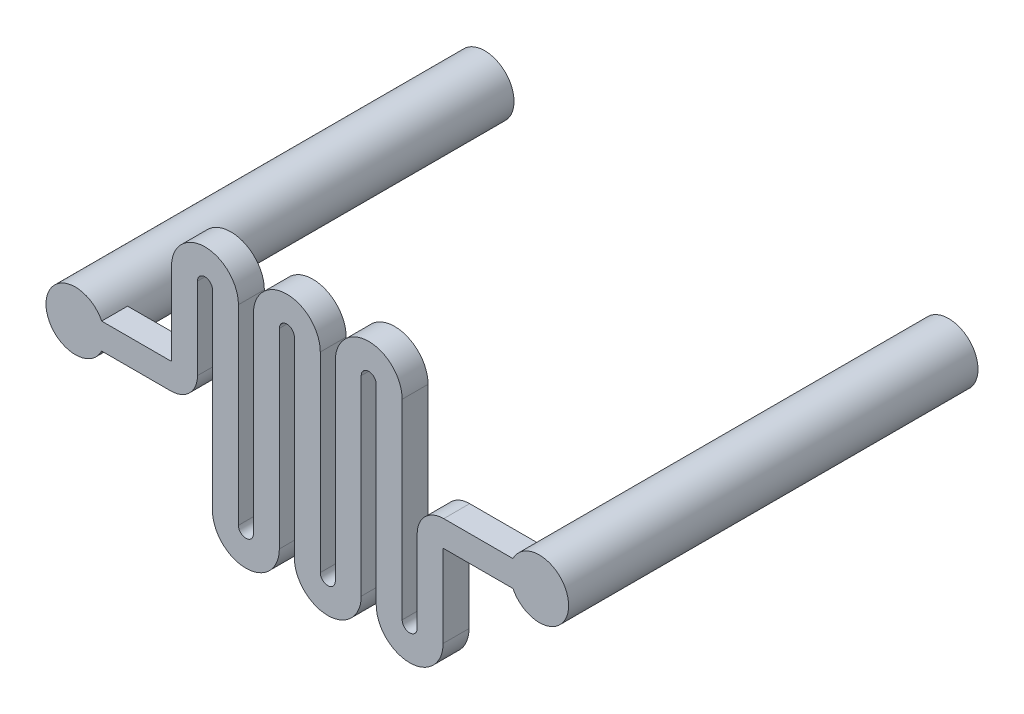
SolidWorks part; units mm, degrees
ref_plane "Front Plane" through (0, 0, 0) normal (0, 0, 1) x (1, 0, 0)
ref_plane "Top Plane" through (0, 0, 0) normal (0, 1, 0) x (1, 0, 0)
ref_plane "Right Plane" through (0, 0, 0) normal (1, 0, 0) x (0, 0, -1)
sketch "Sketch2" plane through (0, 0, 0) normal (0, 0, 1) x (1, 0, 0)
  line L3 (-20.5, -0.95) -> (-13.5, -0.95)
  line L6 (-11.55, 1) -> (-11.55, 7)
  line L9 (-10.45, 7) -> (-10.45, 0)
  line L12 (-10.45, 0) -> (-10.45, -7)
  line L15 (-5.55, -7) -> (-5.55, 0)
  line L18 (-5.55, 0) -> (-5.55, 7)
  line L21 (-4.45, 7) -> (-4.45, 0)
  line L22 (-4.45, 0) -> (-4.45, -7)
  line L23 (0.45, -7) -> (0.45, 0)
  line L24 (0.45, 0) -> (0.45, 7)
  line L25 (1.55, 7) -> (1.55, 0)
  line L26 (1.55, 0) -> (1.55, -7)
  line L27 (6.45, -7) -> (6.45, -1)
  line L28 (6.5, -0.95) -> (13.5, -0.95)
  line L29 (-20.5, 0.95) -> (-13.5, 0.95)
  line L30 (-13.45, 1) -> (-13.45, 7)
  line L31 (-8.55, 7) -> (-8.55, 0)
  line L32 (-8.55, 0) -> (-8.55, -7)
  line L33 (-7.45, -7) -> (-7.45, 0)
  line L34 (-7.45, 0) -> (-7.45, 7)
  line L35 (-2.55, 7) -> (-2.55, 0)
  line L36 (-2.55, 0) -> (-2.55, -7)
  line L37 (-1.45, -7) -> (-1.45, 0)
  line L38 (-1.45, 0) -> (-1.45, 7)
  line L39 (3.45, 7) -> (3.45, 0)
  line L40 (3.45, 0) -> (3.45, -7)
  line L41 (4.55, -7) -> (4.55, -1)
  line L42 (6.5, 0.95) -> (13.5, 0.95)
  arc A0 (13.5, -0.95) -> (13.5, 0.95) centre (13.5, 0) ccw
  arc A8 (-11.55, 1) -> (-13.5, -0.95) centre (-13.5, 1) cw
  arc A9 (-11.55, 7) -> (-10.45, 7) centre (-11, 7) cw
  arc A10 (-10.45, -7) -> (-5.55, -7) centre (-8, -7) ccw
  arc A11 (-5.55, 7) -> (-4.45, 7) centre (-5, 7) cw
  arc A12 (-4.45, -7) -> (0.45, -7) centre (-2, -7) ccw
  arc A13 (0.45, 7) -> (1.55, 7) centre (1, 7) cw
  arc A14 (1.55, -7) -> (6.45, -7) centre (4, -7) ccw
  arc A15 (6.45, -1) -> (6.5, -0.95) centre (6.5, -1) cw
  arc A16 (-13.45, 1) -> (-13.5, 0.95) centre (-13.5, 1) cw
  arc A17 (-13.45, 7) -> (-8.55, 7) centre (-11, 7) cw
  arc A18 (-8.55, -7) -> (-7.45, -7) centre (-8, -7) ccw
  arc A19 (-7.45, 7) -> (-2.55, 7) centre (-5, 7) cw
  arc A20 (-2.55, -7) -> (-1.45, -7) centre (-2, -7) ccw
  arc A21 (-1.45, 7) -> (3.45, 7) centre (1, 7) cw
  arc A22 (3.45, -7) -> (4.55, -7) centre (4, -7) ccw
  arc A23 (4.55, -1) -> (6.5, 0.95) centre (6.5, -1) cw
  arc A24 (-20.5, 0.95) -> (-20.5, -0.95) centre (-20.5, 0) ccw
  point P4 (0, 0)
  point P32 (5.5, 0)
  point P35 (-12.5, 0)
extrude "Boss-Extrude1" add sketch "Sketch2" along normal blind 1.9
ref_plane "Plane1" through (0, 0, 0) normal (0, 1, 0) x (1, 0, 0)
ref_plane "Plane2" through (0, 0, 0) normal (0, 1, 0) x (1, 0, 0)
sketch "Sketch4" plane through (0, 0, 0) normal (0, 1, 0) x (1, 0, 0)
  line L1 (13.5, 28.1) -> (15.65, 28.1)
  line L2 (13.5, -1.9) -> (13.5, 28.1)
  line L3 (15.65, 28.1) -> (15.65, -1.9)
  line L7 (15.65, -1.9) -> (13.5, -1.9)
  dimension "D1" = 2.15
  dimension "D4" = 30
sketch "Sketch5" plane through (0, 0, 0) normal (0, 1, 0) x (1, 0, 0)
  line L0 (-20.5, -1.9) -> (-22.65, -1.9)
  line L1 (-22.65, -1.9) -> (-22.65, 28.1)
  line L2 (-22.65, 28.1) -> (-20.5, 28.1)
  line L3 (-20.5, 28.1) -> (-20.5, -1.9)
  dimension "D1" = 2.15
  dimension "D2" = 30
revolve "Revolve1" add sketch "Sketch5" angle 360 about L3
revolve "Revolve2" add sketch "Sketch4" angle 360 about L2
sketch "Sketch6" plane through (0, 0, -28.1) normal (0, 0, -1) x (-1, 0, 0)
  circle A0 centre (-13.5, 0) radius 1.5
  circle A1 centre (20.5, 0) radius 1.5
  dimension "D1" = 3
  dimension "D2" = 3
extrude "Cut-Extrude1" cut sketch "Sketch6" against normal blind 29
